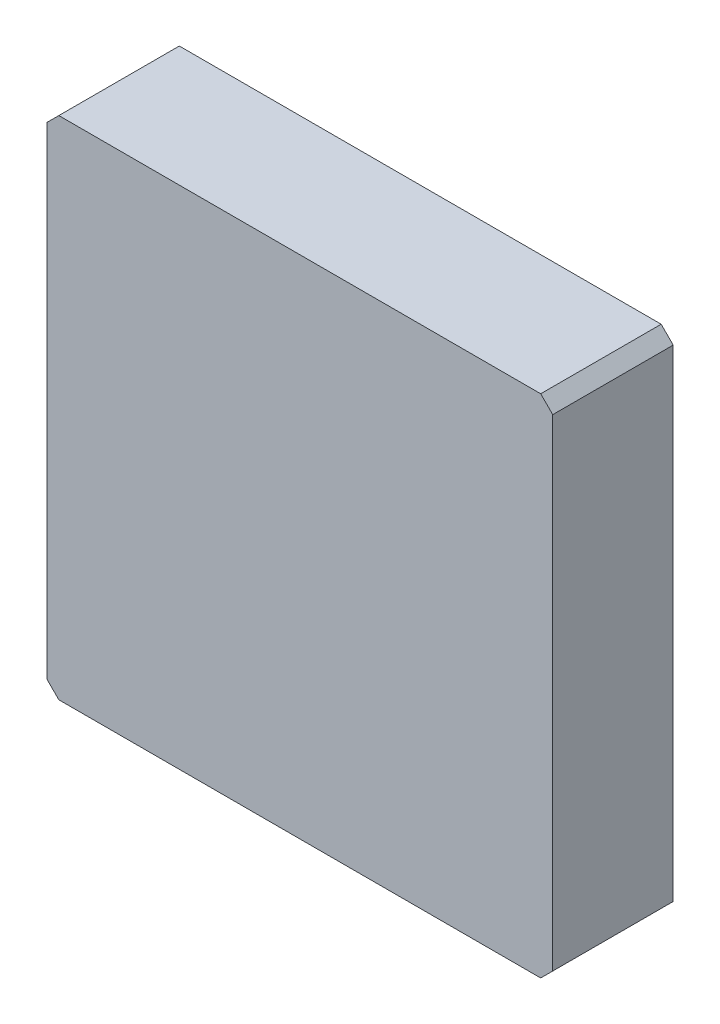
SolidWorks part; units mm, degrees
material "1060 Alloy"
ref_plane "Front Plane" through (0, 0, 0) normal (0, 0, 1) x (1, 0, 0)
ref_plane "Top Plane" through (0, 0, 0) normal (0, 1, 0) x (1, 0, 0)
ref_plane "Right Plane" through (0, 0, 0) normal (1, 0, 0) x (0, 0, -1)
sketch "Sketch1" plane through (0, 0, 0) normal (0, 0, 1) x (1, 0, 0)
  line L0 (-21, 20) -> (-20, 21)
  line L1 (-20, 21) -> (20, 21)
  line L2 (-21, 20) -> (-21, -20)
  line L3 (-20, -21) -> (20, -21)
  line L4 (21, 20) -> (21, -20)
  line L5 (-21, 21) -> (21, -21) construction
  line L6 (-21, -21) -> (21, 21) construction
  line L7 (20, 21) -> (21, 20)
  line L8 (21, -20) -> (20, -21)
  line L9 (-21, -20) -> (-20, -21)
  point P0 (0, 0)
  dimension "D1" = 42
  dimension "D2" = 42
extrude "Boss-Extrude1" add sketch "Sketch1" along normal blind 10
